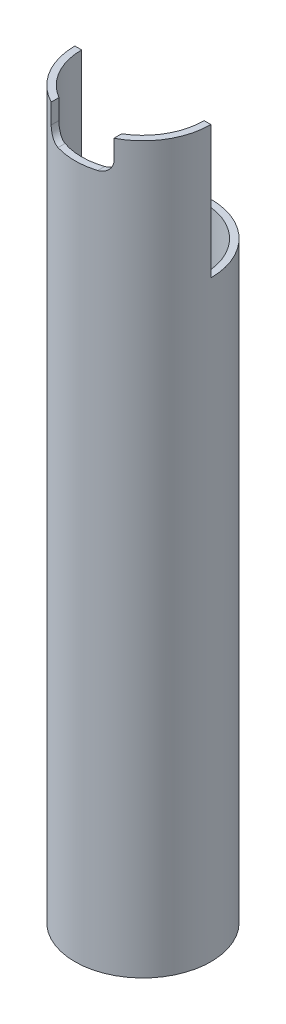
SolidWorks part; units mm, degrees
material "6061-T6 (SS)"
ref_plane "Front Plane" through (0, 0, 0) normal (0, 0, 1) x (1, 0, 0)
ref_plane "Top Plane" through (0, 0, 0) normal (0, 1, 0) x (1, 0, 0)
ref_plane "Right Plane" through (0, 0, 0) normal (1, 0, 0) x (0, 0, -1)
sketch "Sketch1" plane through (0, 0, 0) normal (0, 1, 0) x (1, 0, 0)
  circle A0 centre (0, 0) radius 14.0975
  circle A1 centre (0, 0) radius 12.7
  dimension "D1" = 25.4
  dimension "D2" = 28.195
extrude "Boss-Extrude1" add sketch "Sketch1" along normal blind 152.5
sketch "Sketch2" plane through (0, 152.5, 0) normal (0, 1, 0) x (1, 0, 0)
  line L1 (-14.0975, 0) -> (15.3413, 0)
  line L2 (-14.0975, 0) -> (-14.0975, 15.5555)
  line L3 (-14.0975, 15.5555) -> (15.3413, 15.5555)
  line L4 (15.3413, 0) -> (15.3413, 15.5555)
  circle A0 centre (0, 0) radius 14.0975 construction
extrude "Cut-Extrude1" cut sketch "Sketch2" against normal blind 27.5
sketch "Sketch3" plane through (0, 152.5, 0) normal (0, 1, 0) x (1, 0, 0)
  line L0 (0, -12.7) -> (0, -14.5) construction
  line L1 (6.5, -14.5) -> (-6.5, -14.5)
  line L5 (6.5, -9.2468) -> (-6.5, -9.2468)
  line L8 (6.5, -14.5) -> (6.5, -9.2468)
  line L10 (-6.5, -9.2468) -> (-6.5, -14.5)
  arc A1 (-12.7, 0) -> (12.7, 0) centre (0, 0) ccw construction
  point P14 (0, -14.5)
extrude "Cut-Extrude2" cut sketch "Sketch3" against normal blind 6.5
fillet "Fillet1" radius 2.38 2 edges at (6.5, 146, 11.7101) (-6.5, 146, 11.7101)
sketch "Sketch4" plane through (0, 0, 0) normal (0, -1, 0) x (1, 0, 0)
  line L5 (-17.1269, -18.5197) -> (18.4681, -18.5197)
  line L6 (-17.1269, -18.5197) -> (-17.1269, 19.242)
  line L7 (-17.1269, 19.242) -> (18.4681, 19.242)
  line L8 (18.4681, -18.5197) -> (18.4681, 19.242)
extrude "Cut-Extrude3" cut sketch "Sketch4" against normal blind 2.25
